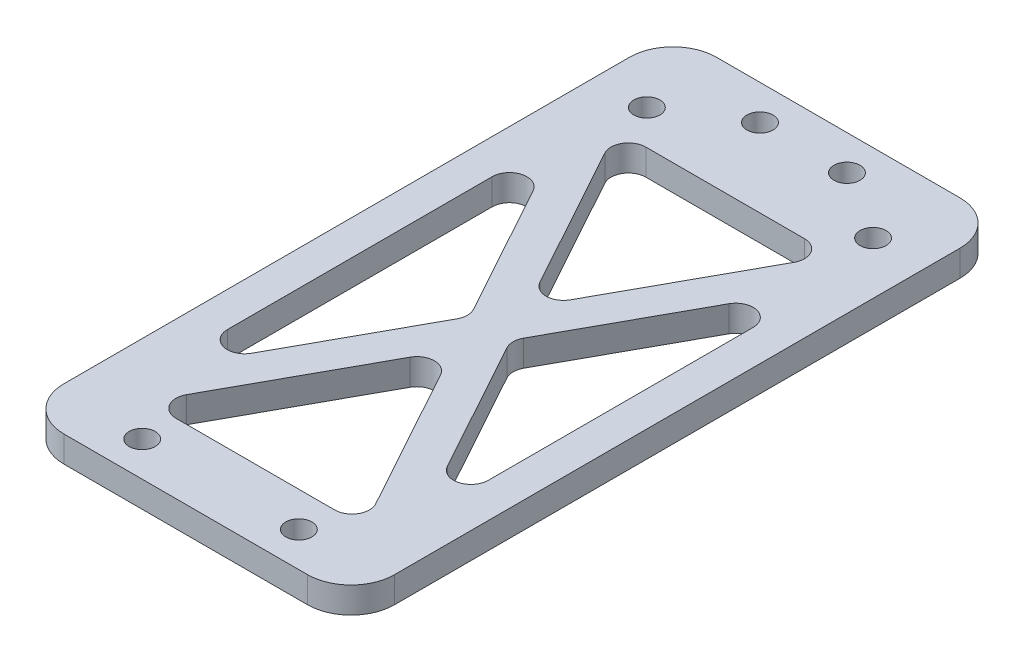
SolidWorks part; units mm, degrees
material "Thornel Mat VMA"
ref_plane "前视基准面" through (0, 0, 0) normal (0, 0, 1) x (1, 0, 0)
ref_plane "上视基准面" through (0, 0, 0) normal (0, 1, 0) x (1, 0, 0)
ref_plane "右视基准面" through (0, 0, 0) normal (1, 0, 0) x (0, 0, -1)
other "Configuration Table"
sketch "草图1" plane through (0, 0, 0) normal (0, 1, 0) x (1, 0, 0)
  line L0 (0, 0) -> (0, 24.8048) construction
  line L1 (-19, -35) -> (19, -35)
  line L2 (-19, -35) -> (-19, 35)
  line L3 (-19, 35) -> (19, 35)
  line L4 (19, -35) -> (19, 35)
  line L5 (-19, -35) -> (19, 35) construction
  line L6 (-19, 35) -> (19, -35) construction
  line L7 (-19, 35) -> (-19, 40)
  line L8 (-15, -27) -> (15, -27)
  line L9 (-15, -27) -> (-15, 27)
  line L10 (-15, 27) -> (15, 27)
  line L11 (15, -27) -> (15, 27)
  line L12 (-15, -27) -> (15, 27) construction
  line L13 (-15, 27) -> (15, -27) construction
  line L14 (-19, 40) -> (19, 40)
  line L15 (19, 40) -> (19, 35)
  circle A0 centre (-13, 31) radius 1.5
  circle A3 centre (13, 31) radius 1.5
  circle A4 centre (9, -31) radius 1.5
  circle A5 centre (-9, -31) radius 1.5
  point P0 (0, 0)
  dimension "D5" = 3
  dimension "D6" = 5
  dimension "D7" = 13
  dimension "D10" = 3
  dimension "D11" = 4
  dimension "D12" = 18
  dimension "D1" = 38
  dimension "D2" = 70
  dimension "D3" = 30
  dimension "D4" = 54
  dimension "D8" = 4
extrude "凸台-拉伸1" add sketch "草图1" along normal blind 3 contours L1 L4 L3 L2 A3 A0 L11 L8 L9 L10 A4 A5 | L15 L14 L7 L3
sketch "草图2" plane through (0, 3, 0) normal (0, 1, 0) x (1, 0, 0)
  line L0 (0, 0) -> (0, 36.8449) construction
  line L1 (0, 0) -> (39.065, 0) construction
  line L2 (12.5, 27) -> (15, 27)
  line L3 (15, -27) -> (15, -23)
  line L5 (12.5, -27) -> (15, -27)
  line L6 (15, 27) -> (15, 23)
  line L8 (15, 23) -> (-12.5, -27)
  line L10 (-12.5, -27) -> (-15, -27)
  line L11 (-15, -27) -> (-15, -23)
  line L13 (-15, -23) -> (12.5, 27)
  line L14 (-15, 23) -> (12.5, -27)
  line L15 (-15, 27) -> (-15, 23)
  line L16 (-12.5, 27) -> (-15, 27)
  line L17 (15, -23) -> (-12.5, 27)
  dimension "D1" = 2.5
  dimension "D2" = 4
  dimension "D3" = 2.5
extrude "凸台-拉伸2" add sketch "草图2" against normal blind 3
fillet "圆角1" radius 2 12 edges at (-15, 1.5, -23) (15, 1.5, -23) (15, 1.5, 23) (-15, 1.5, 23) (12.5, 1.5, 27) (-12.5, 1.5, 27) (12.5, 1.5, -27) (-12.5, 1.5, -27) (-2.35, 1.5, 0) (2.35, 1.5, 0) (0, 1.5, -4.2727) (0, 1.5, 4.2727)
sketch "草图4" plane through (0, 3, 0) normal (0, 1, 0) x (1, 0, 0)
  line L0 (0, 0) -> (0, 51.7257) construction
  line L1 (-19, 40) -> (19, 40) construction
  circle A0 centre (-5, 36) radius 1.5
  circle A1 centre (5, 36) radius 1.5
  dimension "D1" = 3
  dimension "D2" = 10
  dimension "D3" = 4
extrude "切除-拉伸1" cut sketch "草图4" against normal blind 10
fillet "圆角2" radius 5 4 edges at (-19, 1.5, 35) (19, 1.5, 35) (19, 1.5, -40) (-19, 1.5, -40)
